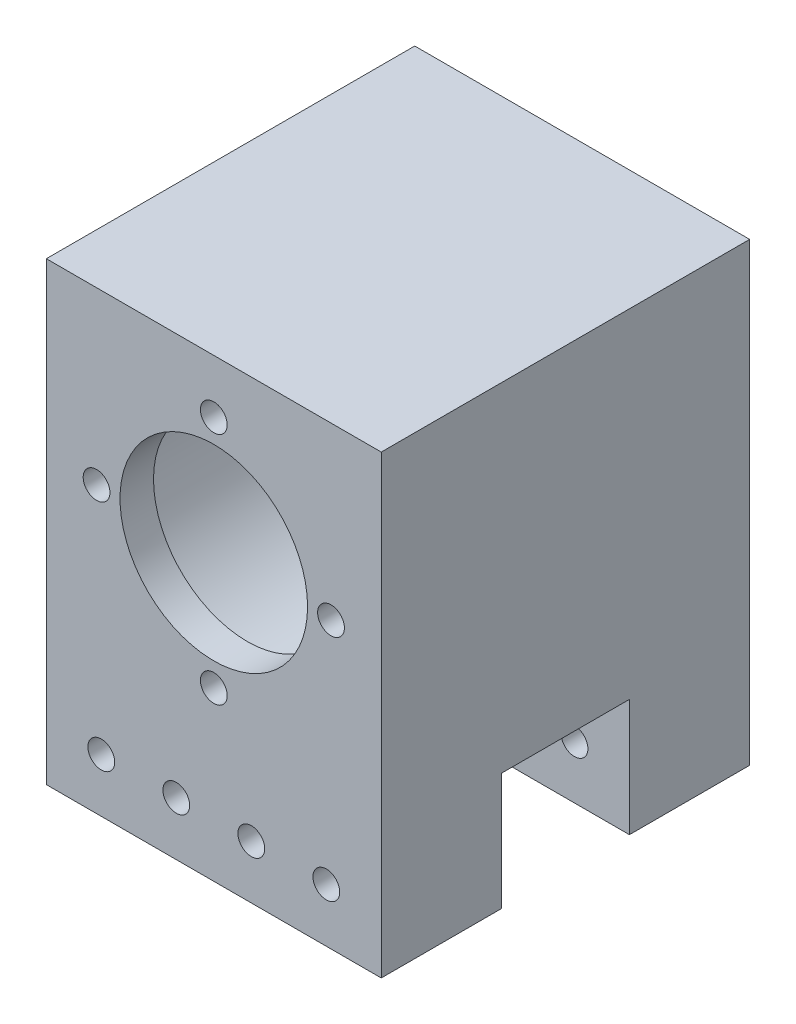
SolidWorks part; units mm, degrees
other "Markup1"
sketch "Sketch6" plane through (25, 68, 27.5) normal (0.3929, 0.5269, 0.7537) x (0.8924, -0.0208, -0.4507)
material "1060 Alloy"
ref_plane "Front Plane" through (0, 0, 0) normal (0, 0, 1) x (1, 0, 0)
ref_plane "Top Plane" through (0, 0, 0) normal (0, 1, 0) x (1, 0, 0)
ref_plane "Right Plane" through (0, 0, 0) normal (1, 0, 0) x (0, 0, -1)
sketch "Sketch1" plane through (0, 0, 0) normal (0, 1, 0) x (1, 0, 0)
  line L1 (-25, -27.5) -> (25, -27.5)
  line L2 (-25, -27.5) -> (-25, 27.5)
  line L3 (-25, 27.5) -> (25, 27.5)
  line L4 (25, -27.5) -> (25, 27.5)
  line L5 (-25, -27.5) -> (25, 27.5) construction
  line L6 (-25, 27.5) -> (25, -27.5) construction
  point P0 (0, 0)
  dimension "D1" = 50
  dimension "D2" = 55
extrude "Boss-Extrude1" add sketch "Sketch1" along normal blind 68
sketch "Sketch2" plane through (0, 0, 27.5) normal (0, 0, 1) x (1, 0, 0)
  line L1 (-25, 68) -> (25, 68) construction
  circle A0 centre (0, 42.5) radius 14
  circle A1 centre (0, 60) radius 2
  circle A2 centre (17.5, 42.5) radius 2
  circle A3 centre (0, 25) radius 2
  circle A4 centre (-17.5, 42.5) radius 2
  point P16 (0, 42.5)
  dimension "D1" = 28
  dimension "D2" = 4
  dimension "D3" = 17.5
  dimension "D4" = 25.5
  dimension "D5" = 4
sketch "Sketch3" plane through (0, 0, -27.5) normal (0, 0, -1) x (-1, 0, 0)
  circle A0 centre (0, 42.5) radius 21.125
  dimension "D1" = 42.25
extrude "Cut-Extrude1" cut sketch "Sketch3" against normal offset from surface (50 mm away) 5 contours A0 up to face at (0, 34, 27.5)
extrude "Cut-Extrude2" cut sketch "Sketch2" against normal through all
sketch "Sketch4" plane through (25, 0, 0) normal (1, 0, 0) x (0, 0, -1)
  line L0 (-27.5, 0) -> (27.5, 0) construction
  line L1 (-9.55, 0) -> (9.55, 0)
  line L2 (-9.55, 0) -> (-9.55, 17.5)
  line L3 (-9.55, 17.5) -> (9.55, 17.5)
  line L4 (9.55, 0) -> (9.55, 17.5)
  line L5 (-27.5, 34) -> (27.5, 34) construction
  line L6 (-27.5, 68) -> (-27.5, 0) construction
  line L7 (27.5, 68) -> (27.5, 0) construction
  point P6 (0, 17.5)
  dimension "D1" = 19.1
  dimension "D2" = 17.5
extrude "Cut-Extrude3" cut sketch "Sketch4" against normal through all
sketch "Sketch5" plane through (0, 0, 27.5) normal (0, 0, 1) x (1, 0, 0)
  line L0 (-25, 0) -> (25, 0) construction
  line L1 (-25, 68) -> (-25, 0) construction
  line L2 (25, 68) -> (25, 0) construction
  circle A0 centre (-16.8, 8) radius 2
  circle A1 centre (-5.6, 8) radius 2
  circle A2 centre (5.6, 8) radius 2
  circle A3 centre (16.8, 8) radius 2
  dimension "D1" = 4
  dimension "D2" = 8
  dimension "D3" = 8.2
  dimension "D5" = 8.2
  dimension "D4" = 4
extrude "Cut-Extrude4" cut sketch "Sketch5" against normal through all
